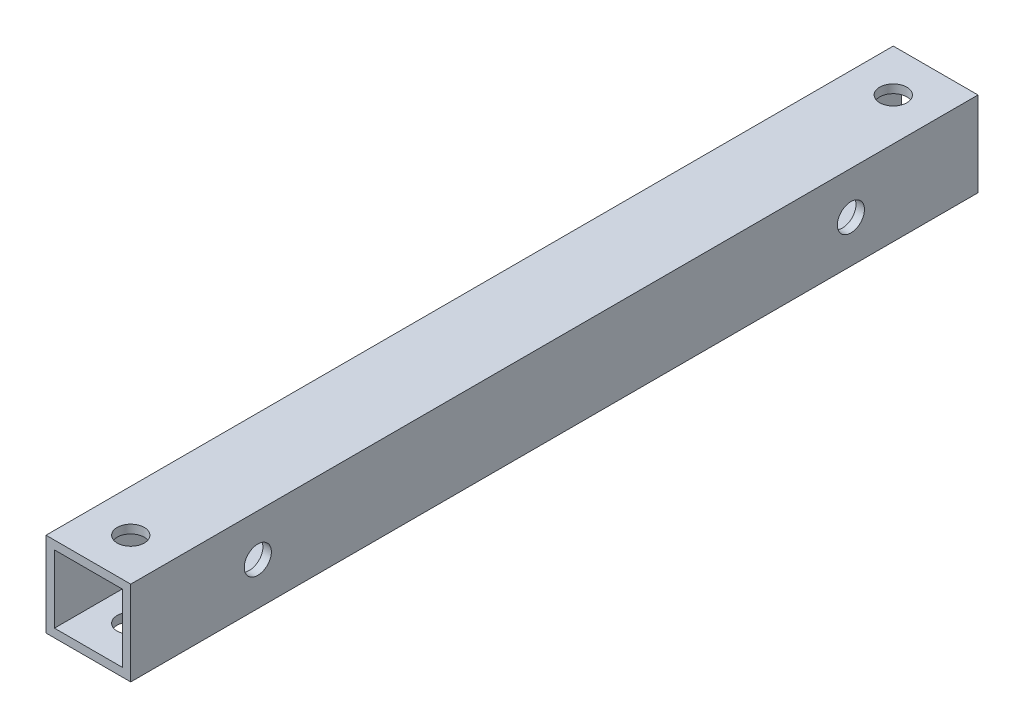
SolidWorks part; units mm, degrees
ref_plane "正面" through (0, 0, 0) normal (0, 0, 1) x (1, 0, 0)
ref_plane "平面" through (0, 0, 0) normal (0, 1, 0) x (1, 0, 0)
ref_plane "右側面" through (0, 0, 0) normal (1, 0, 0) x (0, 0, -1)
sketch "ｽｹｯﾁ1" plane through (0, 0, 0) normal (0, 0, 1) x (1, 0, 0)
  line L0 (-4, 4) -> (-4, -4)
  line L1 (-5, 5) -> (5, 5)
  line L2 (-5, 5) -> (-5, -5)
  line L3 (-5, -5) -> (5, -5)
  line L4 (5, 5) -> (5, -5)
  line L5 (-5, 5) -> (5, -5) construction
  line L6 (-5, -5) -> (5, 5) construction
  line L7 (-4, -4) -> (4, -4)
  line L8 (4, 4) -> (4, -4)
  line L9 (-4, 4) -> (4, 4)
  point P0 (0, 0)
  dimension "D1" = 10
  dimension "D2" = 10
  dimension "D3" = 1
extrude "ﾎﾞｽ - 押し出し1" add sketch "ｽｹｯﾁ1" along normal blind 100
sketch "ｽｹｯﾁ2" plane through (5, 0, 0) normal (1, 0, 0) x (0, 0, -1)
  line L0 (5.5, 0) -> (-5.5, 0) construction
  line L1 (-100, -5) -> (-100, 5) construction
  circle A0 centre (-85, 0) radius 1.6
  circle A1 centre (-15, 0) radius 1.6
  dimension "D1" = 3.2
  dimension "D2" = 3.2
  dimension "D3" = 70
  dimension "D4" = 15
extrude "ｶｯﾄ - 押し出し1" cut sketch "ｽｹｯﾁ2" against normal through all
sketch "ｽｹｯﾁ3" plane through (0, 5, 0) normal (0, 1, 0) x (1, 0, 0)
  line L0 (0, -5.5) -> (0, 5.5) construction
  line L1 (5, -100) -> (-5, -100) construction
  line L2 (-5.5, 0) -> (5.5, 0) construction
  circle A0 centre (0, -95) radius 1.6
  circle A1 centre (0, -5) radius 1.6
  dimension "D1" = 3.2
  dimension "D2" = 5
  dimension "D3" = 3.2
  dimension "D4" = 5
extrude "ｶｯﾄ - 押し出し2" cut sketch "ｽｹｯﾁ3" against normal blind 100
